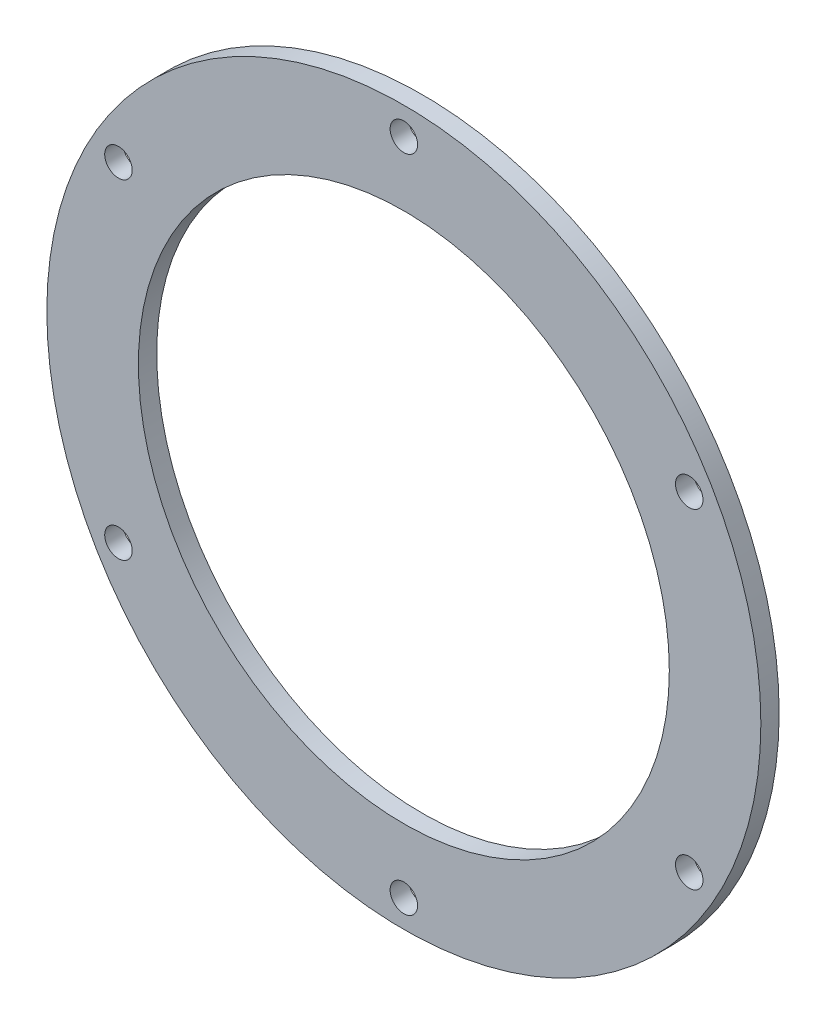
SolidWorks part; units mm, degrees
material "AISI 1035 Steel (SS)"
ref_plane "Front Plane" through (0, 0, 0) normal (0, 0, 1) x (1, 0, 0)
ref_plane "Top Plane" through (0, 0, 0) normal (0, 1, 0) x (1, 0, 0)
ref_plane "Right Plane" through (0, 0, 0) normal (1, 0, 0) x (0, 0, -1)
sketch "Sketch1" plane through (0, 0, 0) normal (0, 0, 1) x (1, 0, 0)
  circle A0 centre (0, 0) radius 29
  circle A1 centre (0, 0) radius 36 construction
  circle A2 centre (0, 0) radius 39
  circle A3 centre (0, 36) radius 1.5
  circle A4 centre (0, 0) radius 29
  circle A5 centre (31.1769, 18) radius 1.5
  circle A6 centre (0, 0) radius 29
  circle A7 centre (31.1769, -18) radius 1.5
  circle A8 centre (0, 0) radius 29
  circle A9 centre (0, -36) radius 1.5
  circle A10 centre (0, 0) radius 29
  circle A11 centre (-31.1769, -18) radius 1.5
  circle A12 centre (0, 0) radius 29
  circle A13 centre (-31.1769, 18) radius 1.5
  point P25 (0, 0)
  dimension "D1" = 78
  dimension "D2" = 58
  dimension "D3" = 72
  dimension "D4" = 3
  dimension "D5" = 6
extrude "Boss-Extrude2" add sketch "Sketch1" along normal blind 2 contours A2 A13 A11 A9 A7 A5 A3 A0
